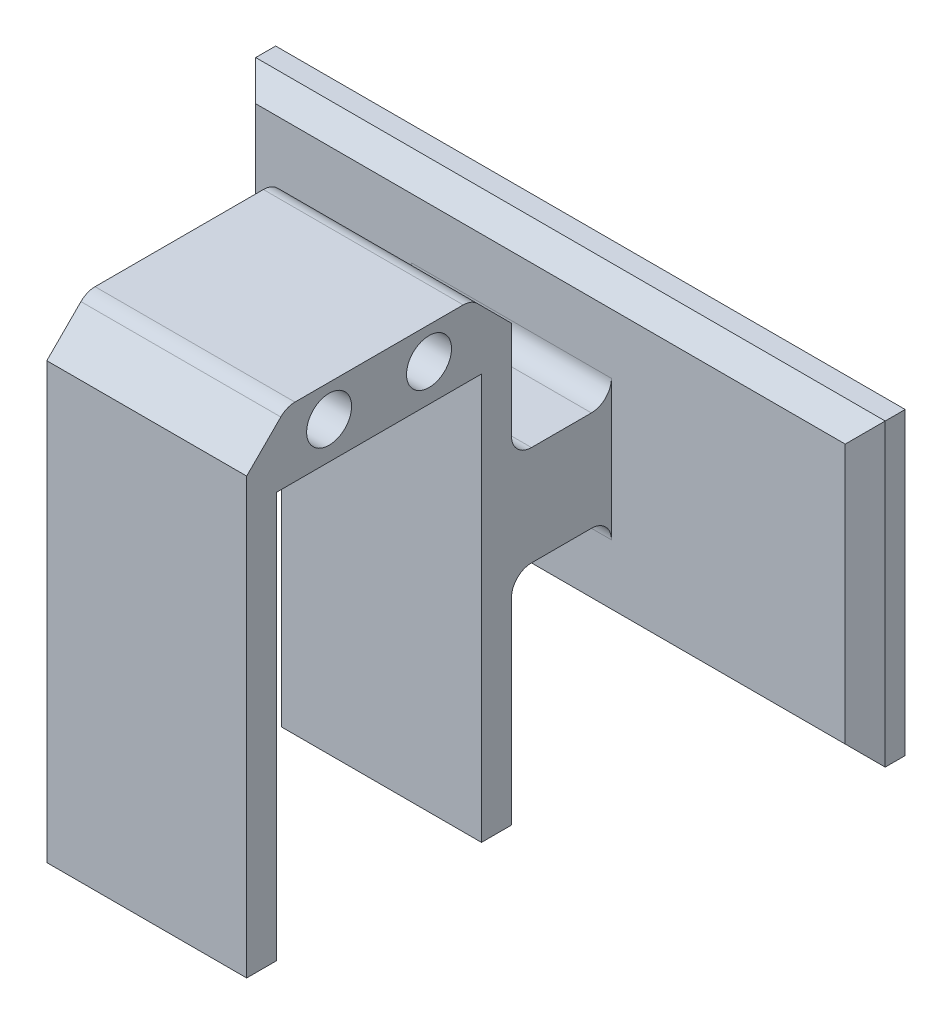
SolidWorks part; units mm, degrees
ref_plane "Front Plane" through (0, 0, 0) normal (0, 0, 1) x (1, 0, 0)
ref_plane "Top Plane" through (0, 0, 0) normal (0, 1, 0) x (1, 0, 0)
ref_plane "Right Plane" through (0, 0, 0) normal (1, 0, 0) x (0, 0, -1)
sketch "Sketch1" plane through (0, 0, 0) normal (1, 0, 0) x (0, 0, -1)
  line L0 (-10.25, 20.3) -> (10.25, 20.3)
  line L1 (-10.25, -20.3) -> (10.25, -20.3)
  line L2 (-10.25, -20.3) -> (-10.25, 20.3)
  line L4 (10.25, -20.3) -> (10.25, 20.3)
  line L5 (-10.25, -20.3) -> (-13.25, -20.3)
  line L6 (-13.25, -20.3) -> (-13.25, 29.7)
  line L7 (-13.25, 29.7) -> (13.25, 29.7)
  line L8 (10.25, -20.3) -> (13.25, -20.3)
  line L11 (-10.05, 20.1) -> (10.05, 20.1)
  line L13 (13.25, -20.3) -> (13.25, 29.7)
  point P5 (0, 20.3)
  point P6 (-10.25, 0)
  line B0 (-8.8772, 20.1) -> (-10.8742, 20.1) construction
  line B1 (7.4, 20.1) -> (11.2713, 20.1) construction
  line B2 (10.05, 18.0597) -> (10.05, 22.3295) construction
  line B3 (-3.2, -20.1) -> (-12.1258, -20.1) construction
  line B4 (-10.05, -15.1145) -> (-10.05, -21.3251) construction
  line B5 (-10.05, -20.1) -> (10.05, -20.1)
  line B6 (-10.05, -20.1) -> (-10.05, 20.1)
  line B7 (10.05, -20.1) -> (10.05, 20.1)
  circle B8 centre (-5, 24) radius 2.25
  circle B9 centre (5, 24) radius 2.25
  dimension "D1" = 0.2
  dimension "D2" = 0.2
  dimension "D3" = 0.2
  dimension "D4" = 0.2
  dimension "D5" = 3
  dimension "D6" = 50
  dimension "D7" = 3
sketch_block_instance "Block1-1"
sketch_block "Block1"
extrude "Boss-Extrude1" add sketch "Sketch1" along normal blind 20 contours L8 L13 L7 L6 L5 L2 L0 L4 B9 B8
sketch "Sketch2" plane through (0, 0, 0) normal (-1, 0, 0) x (0, 0, 1)
  circle A0 centre (-5, 24) radius 2.25
  circle A1 centre (5, 24) radius 2.25
extrude "Boss-Extrude2" add sketch "Sketch2" against normal blind 10
sketch "Sketch4" plane through (20, 0, 0) normal (1, 0, 0) x (0, 0, -1)
  line L0 (13.25, -20.3) -> (13.25, 29.7) construction
  line L1 (-13.25, 29.7) -> (13.25, 29.7)
  line L2 (-13.25, 29.7) -> (-13.25, 27.2)
  line L3 (-13.25, 27.2) -> (13.25, 27.2)
  line L4 (13.25, 29.7) -> (13.25, 27.2)
  dimension "D1" = 2.5
extrude "Cut-Extrude1" cut sketch "Sketch4" against normal through all
chamfer "Chamfer2" distance 4 angle 45 1 edges at (10, 27.2, -13.25)
chamfer "Chamfer3" distance 4 angle 45 1 edges at (10, 27.2, 13.25)
fillet "Fillet4" radius 2 2 edges at (10, 27.2, -9.25) (10, 27.2, 9.25)
sketch "Sketch7" plane through (20, 0, 0) normal (1, 0, 0) x (0, 0, -1)
  line L0 (13.25, -20.3) -> (13.25, 23.2) construction
  line L3 (23.25, 1.4232) -> (13.25, 1.4232)
  line L6 (13.25, 11.4232) -> (23.25, 11.4232)
  line L8 (23.25, 11.4232) -> (23.25, 1.4232)
  line L9 (13.25, 11.4232) -> (13.25, 1.4232)
  point P7 (0, 0)
  dimension "D1" = 10
extrude "Boss-Extrude5" add sketch "Sketch7" against normal up to surface (20 mm away) up to face at (0, 9.4758, 0)
fillet "Fillet6" radius 2 2 edges at (10, 11.4232, -13.25) (10, 1.4232, -13.25)
sketch "Sketch8" plane through (0, 0, -23.25) normal (0, 0, -1) x (-1, 0, 0)
  line L1 (-45.4, 21.4232) -> (17.6, 21.4232)
  line L2 (-45.4, 21.4232) -> (-45.4, -8.5768)
  line L3 (-45.4, -8.5768) -> (17.6, -8.5768)
  line L4 (17.6, 21.4232) -> (17.6, -8.5768)
  line L5 (0, 11.4232) -> (-20, 11.4232) construction
  line L7 (-13.9, 11.4232) -> (-13.9, 1.4232) construction
  line L8 (-20, 1.4232) -> (-20, 11.4232) construction
  line L9 (-20, 6.4232) -> (0, 6.4232) construction
  line L10 (0, 11.4232) -> (0, 1.4232) construction
  line L11 (0, 1.4232) -> (-20, 1.4232) construction
  point P10 (-13.9, 21.4232)
  point P17 (-45.4, 6.4232)
  dimension "D1" = 63
  dimension "D2" = 30
  dimension "D3" = 6.1
extrude "Boss-Extrude6" add sketch "Sketch8" along normal blind 4
chamfer "Chamfer4" distance 2 angle 45 4 edges at (-17.6, 6.4232, -23.25) (13.9, -8.5768, -23.25) (45.4, 6.4232, -23.25) (13.9, 21.4232, -23.25)
fillet "Fillet7" radius 2 2 edges at (10, 11.4232, -23.25) (10, 1.4232, -23.25)
